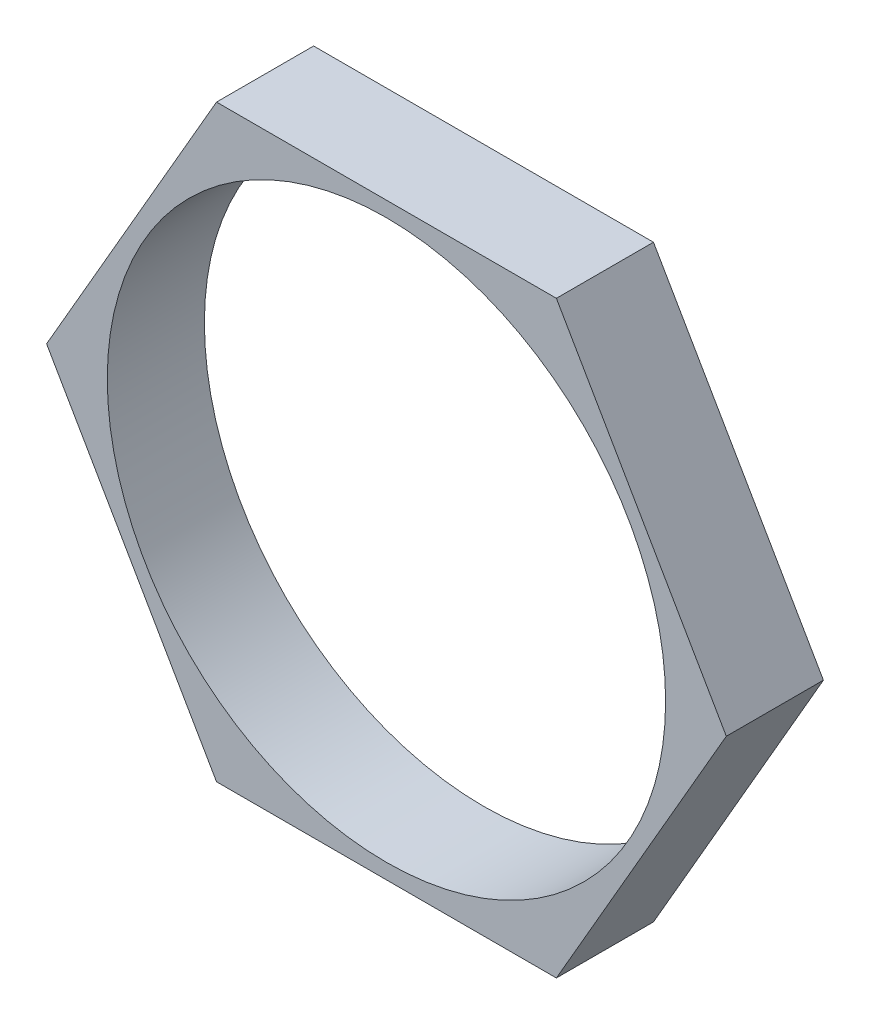
SolidWorks part; units mm, degrees
ref_plane "前视基准面" through (0, 0, 0) normal (0, 0, 1) x (1, 0, 0)
ref_plane "上视基准面" through (0, 0, 0) normal (0, 1, 0) x (1, 0, 0)
ref_plane "右视基准面" through (0, 0, 0) normal (1, 0, 0) x (0, 0, -1)
sketch "草图1" plane through (0, 0, 0) normal (0, 0, 1) x (1, 0, 0)
  line L1 (7, 0) -> (3.5, 6.0622)
  line L2 (3.5, 6.0622) -> (-3.5, 6.0622)
  line L3 (-3.5, 6.0622) -> (-7, 0)
  line L4 (-7, 0) -> (-3.5, -6.0622)
  line L5 (-3.5, -6.0622) -> (3.5, -6.0622)
  line L6 (3.5, -6.0622) -> (7, 0)
  circle A0 centre (0, 0) radius 5.75
  circle A1 centre (0, 0) radius 6.0622 construction
extrude "凸台-拉伸1" add sketch "草图1" along normal blind 2
